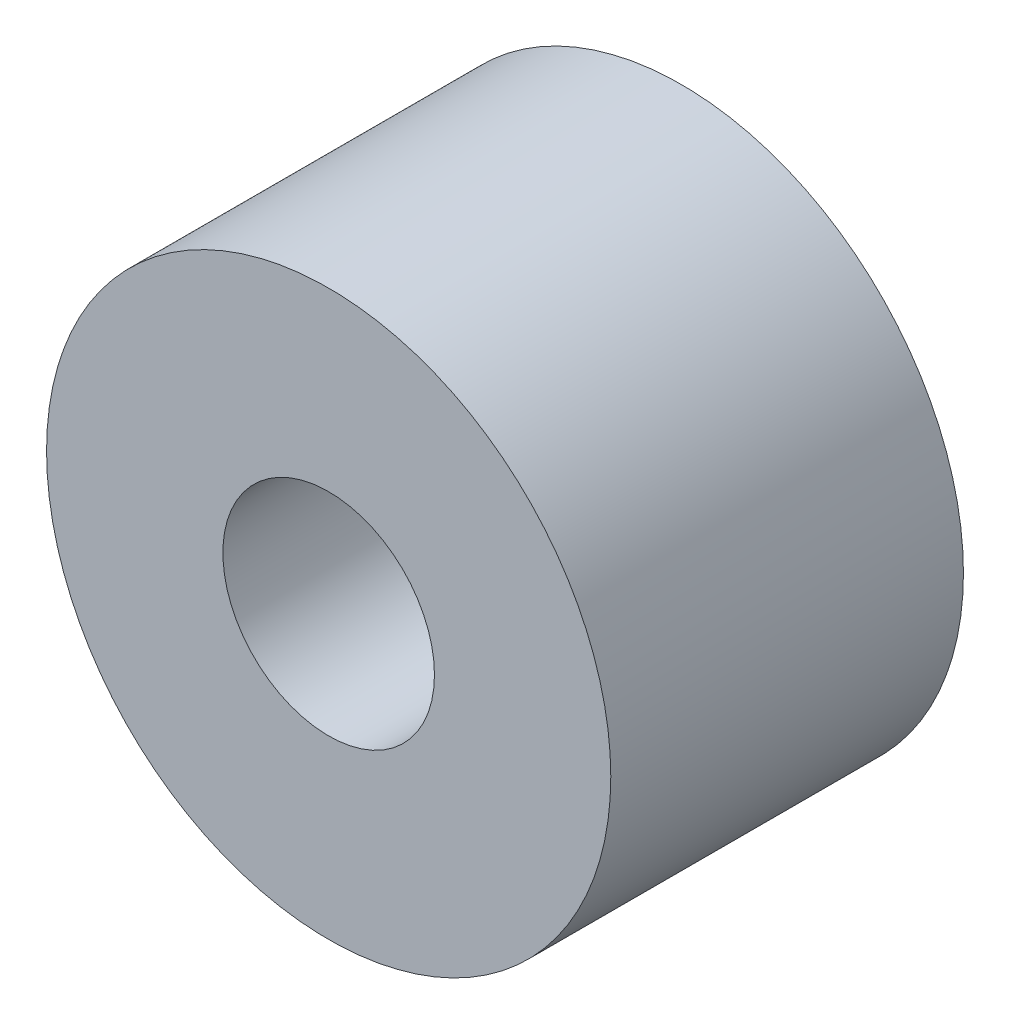
SolidWorks part; units mm, degrees
ref_plane "Front Plane" through (0, 0, 0) normal (0, 0, 1) x (1, 0, 0)
ref_plane "Top Plane" through (0, 0, 0) normal (0, 1, 0) x (1, 0, 0)
ref_plane "Right Plane" through (0, 0, 0) normal (1, 0, 0) x (0, 0, -1)
sketch "Sketch2" plane through (0, 0, 0) normal (0, 0, 1) x (1, 0, 0)
  circle A0 centre (0, 0) radius 4
  circle A1 centre (0, 0) radius 1.5
  dimension "D1" = 8
  dimension "D2" = 3
extrude "Boss-Extrude1" add sketch "Sketch2" along normal blind 5
